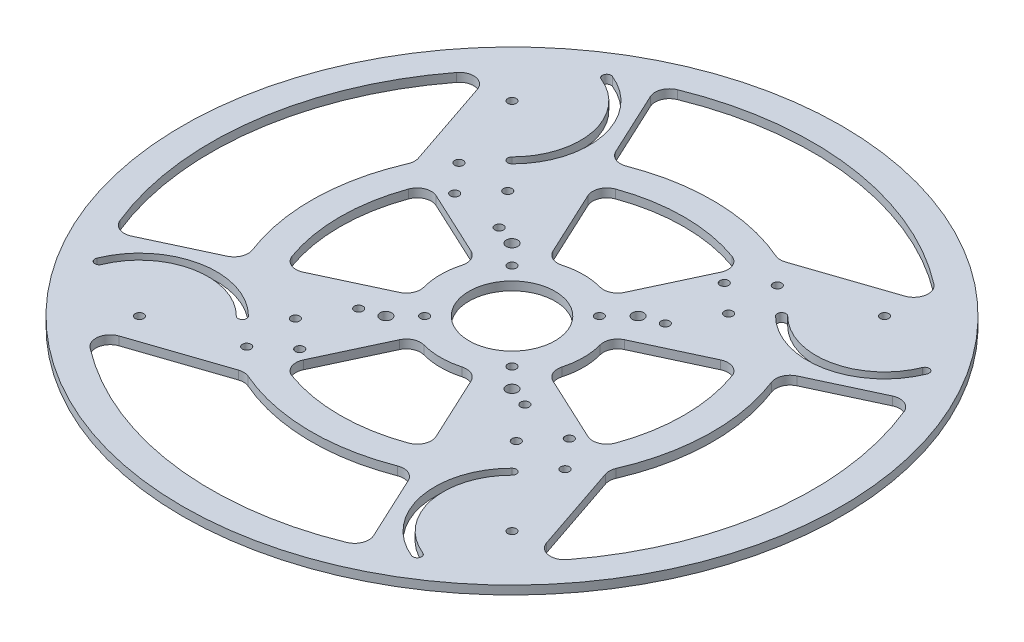
SolidWorks part; units mm, degrees
material "Acrylic (Medium-high impact)"
ref_plane "Front Plane" through (0, 0, 0) normal (0, 0, 1) x (1, 0, 0)
ref_plane "Top Plane" through (0, 0, 0) normal (0, 1, 0) x (1, 0, 0)
ref_plane "Right Plane" through (0, 0, 0) normal (1, 0, 0) x (0, 0, -1)
sketch "Sketch1" plane through (0, 0, 0) normal (0, 1, 0) x (1, 0, 0)
  line L0 (-1000, 0) -> (49000, 0) construction
  line L1 (0, -1000) -> (0, 49000) construction
  line L2 (0, 0) -> (42.8084, 42.8084) construction
  line L3 (0, 0) -> (-54.2199, 54.2199) construction
  line L4 (-65, 65) -> (-65, 95.2779) construction
  line L5 (-65, 65) -> (-52.946, 94.8346) construction
  line L6 (37.0395, 38.5395) -> (37.0395, 55.5395) construction
  line L7 (38.5395, -37.0395) -> (55.5395, -37.0395) construction
  line L8 (-37.0395, -38.5395) -> (-37.0395, -55.5395) construction
  line L9 (-38.5395, 37.0395) -> (-55.5395, 37.0395) construction
  line L10 (0, 0) -> (141.3401, 65.908) construction
  line L11 (0, 0) -> (140.0342, -65.299) construction
  line L12 (26.8089, 12.5012) -> (49.6405, 23.1478)
  line L13 (26.8089, -12.5012) -> (49.6405, -23.1478)
  line L14 (67.8219, 31.6259) -> (90.5174, 42.209)
  line L15 (64.0701, -31.4434) -> (74.5687, -62.5154)
  line L16 (0, 0) -> (130.8105, 60.9979) construction
  line L17 (0, 0) -> (130.9594, -120.0022) construction
  line L18 (12.5012, -26.8089) -> (23.1478, -49.6405)
  line L19 (-12.5012, -26.8089) -> (-23.1478, -49.6405)
  line L20 (-26.8089, -12.5012) -> (-49.6405, -23.1478)
  line L21 (-26.8089, 12.5012) -> (-49.6405, 23.1478)
  line L22 (-12.5012, 26.8089) -> (-23.1478, 49.6405)
  line L23 (12.5012, 26.8089) -> (23.1478, 49.6405)
  line L24 (31.6259, -67.8219) -> (42.209, -90.5174)
  line L25 (-31.4434, -64.0701) -> (-62.5154, -74.5687)
  line L26 (-67.8219, -31.6259) -> (-90.5174, -42.209)
  line L27 (-64.0701, 31.4434) -> (-74.5687, 62.5154)
  line L28 (-31.6259, 67.8219) -> (-42.209, 90.5174)
  line L29 (31.4434, 64.0701) -> (62.5154, 74.5687)
  circle A0 centre (-65, 65) radius 1.5
  arc A1 (-55.485, 88.5505) -> (-47.0395, 47.0395) centre (-65, 65) cw construction
  arc A2 (-45.9788, 45.9788) -> (-54.9231, 89.9412) centre (-65, 65) ccw
  circle A3 centre (-65, 65) radius 25.4 construction
  circle A4 centre (-47.0395, 27.0395) radius 1.5
  circle A5 centre (65, 65) radius 1.5
  circle A6 centre (27.0395, 47.0395) radius 1.5
  circle A7 centre (15.25, 15.25) radius 1.5
  circle A8 centre (22, 22) radius 2
  circle A9 centre (37.0395, 55.5395) radius 1.5
  circle A10 centre (37.0395, 38.5395) radius 1.5
  arc A11 (88.5505, 55.485) -> (47.0395, 47.0395) centre (65, 65) cw construction
  arc A12 (45.9788, 45.9788) -> (89.9412, 54.9231) centre (65, 65) ccw
  arc A13 (48.1001, 48.1001) -> (87.1597, 56.0469) centre (65, 65) ccw
  arc A14 (48.1001, 48.1001) -> (45.9788, 45.9788) centre (47.0395, 47.0395) ccw
  arc A15 (89.9412, 54.9231) -> (87.1597, 56.0469) centre (88.5505, 55.485) ccw
  circle A16 centre (65, -65) radius 1.5
  circle A17 centre (47.0395, -27.0395) radius 1.5
  circle A18 centre (15.25, -15.25) radius 1.5
  circle A19 centre (22, -22) radius 2
  circle A20 centre (55.5395, -37.0395) radius 1.5
  circle A21 centre (38.5395, -37.0395) radius 1.5
  arc A22 (55.485, -88.5505) -> (47.0395, -47.0395) centre (65, -65) cw construction
  arc A23 (45.9788, -45.9788) -> (54.9231, -89.9412) centre (65, -65) ccw
  arc A24 (48.1001, -48.1001) -> (56.0469, -87.1597) centre (65, -65) ccw
  arc A25 (48.1001, -48.1001) -> (45.9788, -45.9788) centre (47.0395, -47.0395) ccw
  arc A26 (54.9231, -89.9412) -> (56.0469, -87.1597) centre (55.485, -88.5505) ccw
  circle A27 centre (-65, -65) radius 1.5
  circle A28 centre (0, 0) radius 15
  circle A29 centre (-15.25, 15.25) radius 1.5
  circle A30 centre (-22, 22) radius 2
  circle A31 centre (-55.5395, 37.0395) radius 1.5
  circle A32 centre (-27.0395, -47.0395) radius 1.5
  circle A33 centre (-15.25, -15.25) radius 1.5
  circle A34 centre (-22, -22) radius 2
  circle A35 centre (-37.0395, -55.5395) radius 1.5
  circle A36 centre (-37.0395, -38.5395) radius 1.5
  arc A37 (-88.5505, -55.485) -> (-47.0395, -47.0395) centre (-65, -65) cw construction
  arc A38 (-45.9788, -45.9788) -> (-89.9412, -54.9231) centre (-65, -65) ccw
  arc A39 (-48.1001, -48.1001) -> (-87.1597, -56.0469) centre (-65, -65) ccw
  arc A40 (-48.1001, -48.1001) -> (-45.9788, -45.9788) centre (-47.0395, -47.0395) ccw
  arc A41 (-89.9412, -54.9231) -> (-87.1597, -56.0469) centre (-88.5505, -55.485) ccw
  circle A42 centre (0, 0) radius 115
  circle A43 centre (29, 24.5) radius 1.5
  circle A44 centre (29, -24.5) radius 1.5
  circle A45 centre (-29, -24.5) radius 1.5
  circle A46 centre (-29, 24.5) radius 1.5
  arc A47 (56.4585, -20.3086) -> (56.4585, 20.3086) centre (0, 0) ccw
  arc A48 (24.1017, 6.6414) -> (24.1017, -6.6414) centre (0, 0) cw
  arc A49 (65.2726, 25.288) -> (64.2198, -27.8534) centre (0, 0) cw
  circle A50 centre (-38.5395, 37.0395) radius 1.5
  arc A51 (97.262, 39.5613) -> (83.2708, -63.9607) centre (0, 0) cw
  arc A52 (97.262, 39.5613) -> (90.5174, 42.209) centre (92.6305, 37.6774) ccw
  arc A53 (65.2726, 25.288) -> (67.8219, 31.6259) centre (69.935, 27.0943) cw
  arc A54 (-48.1001, 48.1001) -> (-56.0469, 87.1597) centre (-65, 65) ccw
  arc A55 (-48.1001, 48.1001) -> (-45.9788, 45.9788) centre (-47.0395, 47.0395) ccw
  arc A56 (-54.9231, 89.9412) -> (-56.0469, 87.1597) centre (-55.485, 88.5505) ccw
  arc A57 (64.2198, -27.8534) -> (64.0701, -31.4434) centre (68.807, -29.8429) ccw
  arc A58 (83.2708, -63.9607) -> (74.5687, -62.5154) centre (79.3056, -60.9149) cw
  arc A59 (24.1017, -6.6414) -> (26.8089, -12.5012) centre (28.922, -7.9697) ccw
  arc A60 (56.4585, -20.3086) -> (49.6405, -23.1478) centre (51.7536, -18.6162) cw
  arc A61 (56.4585, 20.3086) -> (49.6405, 23.1478) centre (51.7536, 18.6162) ccw
  arc A62 (24.1017, 6.6414) -> (26.8089, 12.5012) centre (28.922, 7.9697) cw
  arc A63 (20.3086, -56.4585) -> (23.1478, -49.6405) centre (18.6162, -51.7536) ccw
  arc A64 (6.6414, -24.1017) -> (12.5012, -26.8089) centre (7.9697, -28.922) cw
  arc A65 (6.6414, -24.1017) -> (-6.6414, -24.1017) centre (0, 0) cw
  arc A66 (-6.6414, -24.1017) -> (-12.5012, -26.8089) centre (-7.9697, -28.922) ccw
  arc A67 (-20.3086, -56.4585) -> (-23.1478, -49.6405) centre (-18.6162, -51.7536) cw
  arc A68 (-20.3086, -56.4585) -> (20.3086, -56.4585) centre (0, 0) ccw
  arc A69 (-56.4585, -20.3086) -> (-49.6405, -23.1478) centre (-51.7536, -18.6162) ccw
  arc A70 (-24.1017, -6.6414) -> (-26.8089, -12.5012) centre (-28.922, -7.9697) cw
  arc A71 (-24.1017, -6.6414) -> (-24.1017, 6.6414) centre (0, 0) cw
  arc A72 (-24.1017, 6.6414) -> (-26.8089, 12.5012) centre (-28.922, 7.9697) ccw
  arc A73 (-56.4585, 20.3086) -> (-49.6405, 23.1478) centre (-51.7536, 18.6162) cw
  arc A74 (-56.4585, 20.3086) -> (-56.4585, -20.3086) centre (0, 0) ccw
  arc A75 (-20.3086, 56.4585) -> (-23.1478, 49.6405) centre (-18.6162, 51.7536) ccw
  arc A76 (-6.6414, 24.1017) -> (-12.5012, 26.8089) centre (-7.9697, 28.922) cw
  arc A77 (-6.6414, 24.1017) -> (6.6414, 24.1017) centre (0, 0) cw
  arc A78 (6.6414, 24.1017) -> (12.5012, 26.8089) centre (7.9697, 28.922) ccw
  arc A79 (20.3086, 56.4585) -> (23.1478, 49.6405) centre (18.6162, 51.7536) cw
  arc A80 (20.3086, 56.4585) -> (-20.3086, 56.4585) centre (0, 0) ccw
  arc A81 (25.288, -65.2726) -> (31.6259, -67.8219) centre (27.0943, -69.935) cw
  arc A82 (25.288, -65.2726) -> (-27.8534, -64.2198) centre (0, 0) cw
  arc A83 (-27.8534, -64.2198) -> (-31.4434, -64.0701) centre (-29.8429, -68.807) ccw
  arc A84 (-63.9607, -83.2708) -> (-62.5154, -74.5687) centre (-60.9149, -79.3056) cw
  arc A85 (39.5613, -97.262) -> (-63.9607, -83.2708) centre (0, 0) cw
  arc A86 (39.5613, -97.262) -> (42.209, -90.5174) centre (37.6774, -92.6305) ccw
  arc A87 (-65.2726, -25.288) -> (-67.8219, -31.6259) centre (-69.935, -27.0943) cw
  arc A88 (-65.2726, -25.288) -> (-64.2198, 27.8534) centre (0, 0) cw
  arc A89 (-64.2198, 27.8534) -> (-64.0701, 31.4434) centre (-68.807, 29.8429) ccw
  arc A90 (-83.2708, 63.9607) -> (-74.5687, 62.5154) centre (-79.3056, 60.9149) cw
  arc A91 (-97.262, -39.5613) -> (-83.2708, 63.9607) centre (0, 0) cw
  arc A92 (-97.262, -39.5613) -> (-90.5174, -42.209) centre (-92.6305, -37.6774) ccw
  arc A93 (-25.288, 65.2726) -> (-31.6259, 67.8219) centre (-27.0943, 69.935) cw
  arc A94 (-25.288, 65.2726) -> (27.8534, 64.2198) centre (0, 0) cw
  arc A95 (27.8534, 64.2198) -> (31.4434, 64.0701) centre (29.8429, 68.807) ccw
  arc A96 (63.9607, 83.2708) -> (62.5154, 74.5687) centre (60.9149, 79.3056) cw
  arc A97 (-39.5613, 97.262) -> (63.9607, 83.2708) centre (0, 0) cw
  arc A98 (-39.5613, 97.262) -> (-42.209, 90.5174) centre (-37.6774, 92.6305) ccw
  point P18 (-40.1099, 70.0639)
  point P27 (29, 24.5)
  point P32 (70.0639, 40.1099)
  point P51 (40.1099, -70.0639)
  point P56 (0, 0)
  point P77 (-70.0639, -40.1099)
  point P91 (0, 0)
  point P117 (95.1623, 44.3749)
  point P120 (63.4415, 29.5833)
  point P121 (0, 0)
  point P125 (63.4415, -29.5833)
  point P128 (77.4141, -70.937)
  point P131 (22.6577, -10.5655)
  point P134 (54.3785, -25.3571)
  point P137 (54.3785, 25.3571)
  point P140 (22.6577, 10.5655)
  point P182 (0, 0)
  point P219 (0, 0)
  dimension "D3" = 65
  dimension "D4" = 3
  dimension "D7" = 1.5
  dimension "D8" = 50.8
  dimension "D10" = 8.5
  dimension "D11" = 20
  dimension "D12" = 3
  dimension "D14" = 30
  dimension "D15" = 15.25
  dimension "D16" = 3
  dimension "D17" = 4
  dimension "D20" = 3
  dimension "D24" = 25
  dimension "D25" = 25
  dimension "D26" = 25
  dimension "D27" = 60
  dimension "D28" = 70
  dimension "D33" = 29
  dimension "D34" = 3
  dimension "D37" = 3
  dimension "D38" = 42.5
  dimension "D19" = 4
  dimension "D21" = 230
  dimension "D22" = 24.5
  dimension "D29" = 105
  dimension "D30" = 5
  dimension "D31" = 9.8605
  dimension "D40" = 5
  dimension "D41" = 4
  dimension "D1" = 45
  dimension "D2" = 45
  dimension "D5" = 22
  dimension "D6" = 25.4
  dimension "D9" = 10
  dimension "D18" = 22
  dimension "D32" = 25
  dimension "D35" = 24.5
  dimension "D36" = 17
  dimension "D13" = 8.5
  dimension "D23" = 29
  dimension "D43" = 9.873
  dimension "D42" = 4
extrude "Boss-Extrude3" add sketch "Sketch1" along normal blind 3
sketch "Sketch3" plane through (0, 3, 0) normal (0, 1, 0) x (1, 0, 0)
